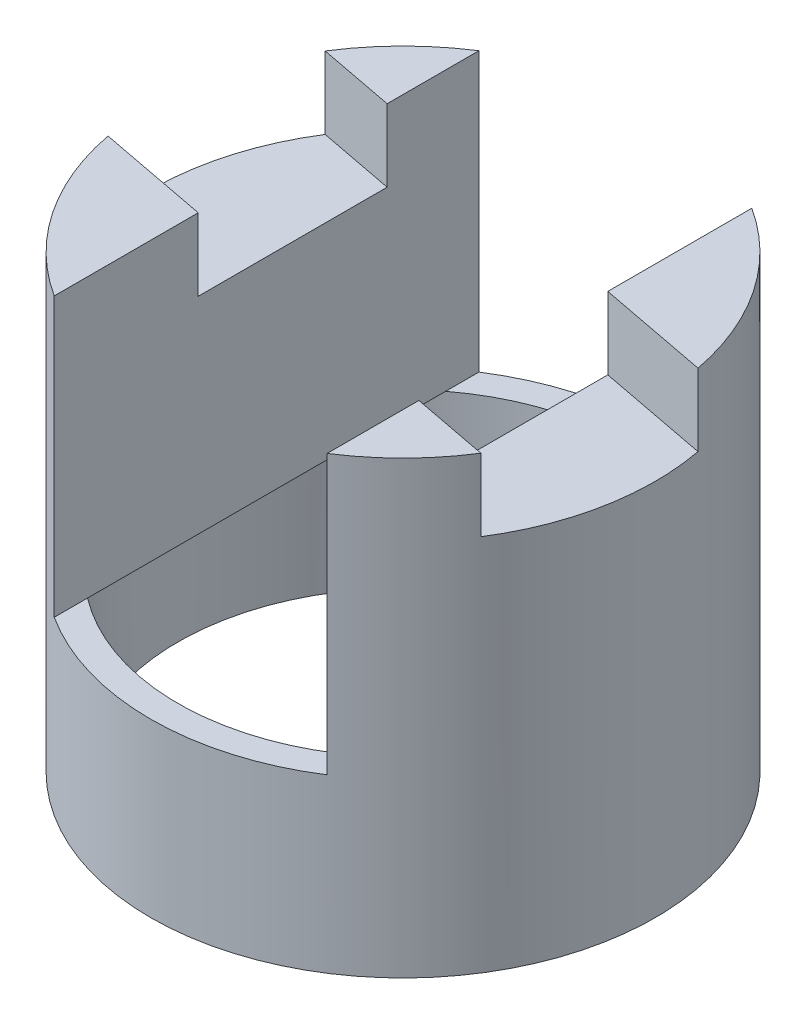
SolidWorks part; units mm, degrees
ref_plane "Front Plane" through (0, 0, 0) normal (0, 0, 1) x (1, 0, 0)
ref_plane "Top Plane" through (0, 0, 0) normal (0, 1, 0) x (1, 0, 0)
ref_plane "Right Plane" through (0, 0, 0) normal (1, 0, 0) x (0, 0, -1)
sketch "Sketch1" plane through (0, 0, 0) normal (0, 1, 0) x (1, 0, 0)
  circle A0 centre (0, 0) radius 18.5
  dimension "D1" = 37
extrude "Boss-Extrude1" add sketch "Sketch1" along normal blind 33
sketch "Sketch4" plane through (0, 0, 0) normal (0, -1, 0) x (1, 0, 0)
  circle A0 centre (0, 0) radius 16.5
  dimension "D1" = 33
extrude "Cut-Extrude3" cut sketch "Sketch4" against normal blind 12.6
sketch "Sketch5" plane through (0, 33, 0) normal (0, 1, 0) x (1, 0, 0)
  line L1 (10, -24.6747) -> (-10, -24.6747)
  line L2 (10, -24.6747) -> (10, 24.6747)
  line L3 (10, 24.6747) -> (-10, 24.6747)
  line L4 (-10, -24.6747) -> (-10, 24.6747)
  line L5 (10, -24.6747) -> (-10, 24.6747) construction
  line L6 (10, 24.6747) -> (-10, -24.6747) construction
  point P0 (0, 0)
  dimension "D1" = 20
extrude "Cut-Extrude4" cut sketch "Sketch5" against normal up to surface (20.4 mm away) up to face at (0, 12.6, -16.5)
sketch "Sketch6" plane through (0, 33, 0) normal (0, 1, 0) x (1, 0, 0)
  line L0 (0, 0) -> (50000, 0) construction
  line L1 (-34.6632, 6.6343) -> (31.7764, -6.0818)
  dimension "D1" = 10.835
ref_plane "Plane2" through (0, 0, 0) normal (-0.188, 0, 0.9822) x (0.9822, 0, 0.188)
sketch "Sketch7" plane through (0, 0, 0) normal (-0.188, 0, 0.9822) x (0.9822, 0, 0.188)
  line L0 (-29.3105, 34.7368) -> (-29.3105, 27.7)
  line L1 (-29.3105, 34.7368) -> (27.1923, 34.7368)
  line L2 (-29.3105, 27.7) -> (27.1923, 27.7)
  line L3 (27.1923, 34.7368) -> (27.1923, 27.7)
  line L4 (7.3546, 12.6) -> (-12.2889, 12.6) construction
  dimension "D1" = 15.1
extrude "Cut-Extrude5" cut sketch "Sketch7" against normal mid plane 13.6
